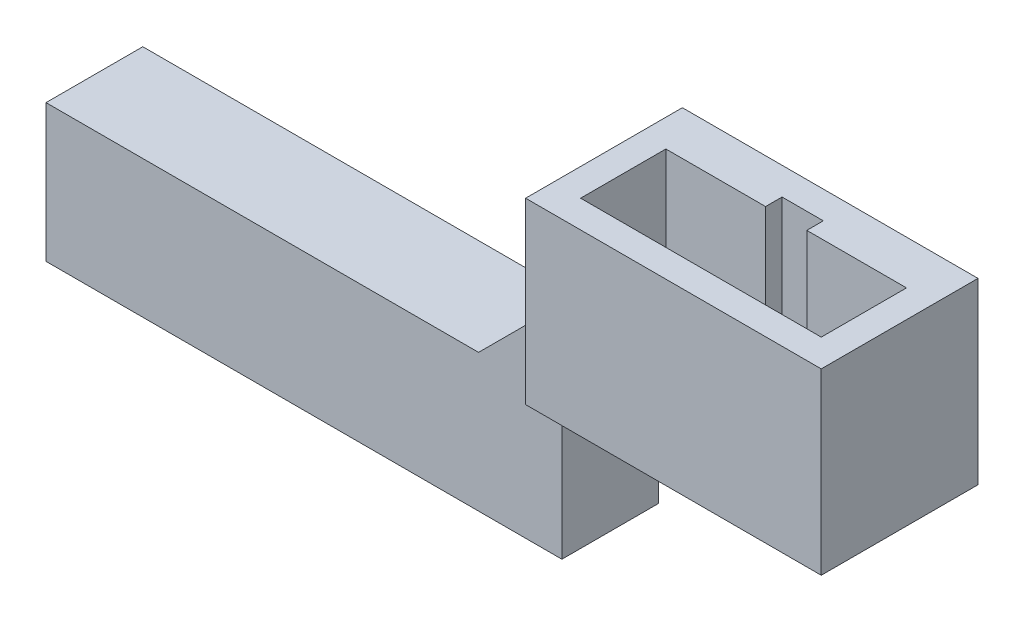
SolidWorks part; units mm, degrees
ref_plane "Front Plane" through (0, 0, 0) normal (0, 0, 1) x (1, 0, 0)
ref_plane "Top Plane" through (0, 0, 0) normal (0, 1, 0) x (1, 0, 0)
ref_plane "Right Plane" through (0, 0, 0) normal (1, 0, 0) x (0, 0, -1)
sketch "Sketch1" plane through (0, 0, 0) normal (0, 1, 0) x (1, 0, 0)
  line L0 (4.04, 3) -> (4.04, 1.5)
  line L1 (0, 0) -> (37.52, 0)
  line L2 (0, 0) -> (0, 7.04)
  line L3 (0, 7.04) -> (37.52, 7.04)
  line L5 (1.5, 3) -> (3, 3)
  line L6 (1.5, 3) -> (1.5, 1.5)
  line L7 (1.5, 1.5) -> (3, 1.5)
  line L8 (3, 3) -> (3, 1.5)
  line L9 (4.04, 3) -> (5.54, 3)
  line L10 (5.54, 3) -> (5.54, 1.5)
  line L11 (4.04, 1.5) -> (5.54, 1.5)
  line L12 (6.58, 3) -> (6.58, 1.5)
  line L13 (6.58, 3) -> (8.08, 3)
  line L14 (8.08, 3) -> (8.08, 1.5)
  line L15 (6.58, 1.5) -> (8.08, 1.5)
  line L16 (9.12, 3) -> (9.12, 1.5)
  line L17 (9.12, 3) -> (10.62, 3)
  line L18 (10.62, 3) -> (10.62, 1.5)
  line L19 (9.12, 1.5) -> (10.62, 1.5)
  line L20 (11.66, 3) -> (11.66, 1.5)
  line L21 (11.66, 3) -> (13.16, 3)
  line L22 (13.16, 3) -> (13.16, 1.5)
  line L23 (11.66, 1.5) -> (13.16, 1.5)
  line L24 (14.2, 3) -> (14.2, 1.5)
  line L25 (14.2, 3) -> (15.7, 3)
  line L26 (15.7, 3) -> (15.7, 1.5)
  line L27 (14.2, 1.5) -> (15.7, 1.5)
  line L28 (16.74, 3) -> (16.74, 1.5)
  line L29 (16.74, 3) -> (18.24, 3)
  line L30 (18.24, 3) -> (18.24, 1.5)
  line L31 (16.74, 1.5) -> (18.24, 1.5)
  line L32 (19.28, 3) -> (19.28, 1.5)
  line L33 (19.28, 3) -> (20.78, 3)
  line L34 (20.78, 3) -> (20.78, 1.5)
  line L35 (19.28, 1.5) -> (20.78, 1.5)
  line L36 (21.82, 3) -> (21.82, 1.5)
  line L37 (21.82, 3) -> (23.32, 3)
  line L38 (23.32, 3) -> (23.32, 1.5)
  line L39 (21.82, 1.5) -> (23.32, 1.5)
  line L40 (24.36, 3) -> (24.36, 1.5)
  line L41 (24.36, 3) -> (25.86, 3)
  line L42 (25.86, 3) -> (25.86, 1.5)
  line L43 (24.36, 1.5) -> (25.86, 1.5)
  line L44 (26.9, 3) -> (26.9, 1.5)
  line L45 (26.9, 3) -> (28.4, 3)
  line L46 (28.4, 3) -> (28.4, 1.5)
  line L47 (26.9, 1.5) -> (28.4, 1.5)
  line L48 (29.44, 3) -> (29.44, 1.5)
  line L49 (29.44, 3) -> (30.94, 3)
  line L50 (30.94, 3) -> (30.94, 1.5)
  line L51 (29.44, 1.5) -> (30.94, 1.5)
  line L52 (31.98, 3) -> (31.98, 1.5)
  line L53 (31.98, 3) -> (33.48, 3)
  line L54 (33.48, 3) -> (33.48, 1.5)
  line L55 (31.98, 1.5) -> (33.48, 1.5)
  line L56 (34.52, 3) -> (34.52, 1.5)
  line L57 (34.52, 3) -> (36.02, 3)
  line L58 (36.02, 3) -> (36.02, 1.5)
  line L59 (34.52, 1.5) -> (36.02, 1.5)
  line L144 (4.04, 5.54) -> (4.04, 4.04)
  line L145 (4.04, 5.54) -> (5.54, 5.54)
  line L146 (5.54, 5.54) -> (5.54, 4.04)
  line L147 (4.04, 4.04) -> (5.54, 4.04)
  line L148 (6.58, 5.54) -> (6.58, 4.04)
  line L149 (6.58, 5.54) -> (8.08, 5.54)
  line L150 (8.08, 5.54) -> (8.08, 4.04)
  line L151 (6.58, 4.04) -> (8.08, 4.04)
  line L152 (9.12, 5.54) -> (9.12, 4.04)
  line L153 (9.12, 5.54) -> (10.62, 5.54)
  line L154 (10.62, 5.54) -> (10.62, 4.04)
  line L155 (9.12, 4.04) -> (10.62, 4.04)
  line L156 (11.66, 5.54) -> (11.66, 4.04)
  line L157 (11.66, 5.54) -> (13.16, 5.54)
  line L158 (13.16, 5.54) -> (13.16, 4.04)
  line L159 (11.66, 4.04) -> (13.16, 4.04)
  line L160 (14.2, 5.54) -> (14.2, 4.04)
  line L161 (14.2, 5.54) -> (15.7, 5.54)
  line L162 (15.7, 5.54) -> (15.7, 4.04)
  line L163 (14.2, 4.04) -> (15.7, 4.04)
  line L164 (16.74, 5.54) -> (16.74, 4.04)
  line L165 (16.74, 5.54) -> (18.24, 5.54)
  line L166 (18.24, 5.54) -> (18.24, 4.04)
  line L167 (16.74, 4.04) -> (18.24, 4.04)
  line L168 (19.28, 5.54) -> (19.28, 4.04)
  line L169 (19.28, 5.54) -> (20.78, 5.54)
  line L170 (20.78, 5.54) -> (20.78, 4.04)
  line L171 (19.28, 4.04) -> (20.78, 4.04)
  line L172 (21.82, 5.54) -> (21.82, 4.04)
  line L173 (21.82, 5.54) -> (23.32, 5.54)
  line L174 (23.32, 5.54) -> (23.32, 4.04)
  line L175 (21.82, 4.04) -> (23.32, 4.04)
  line L176 (24.36, 5.54) -> (24.36, 4.04)
  line L177 (24.36, 5.54) -> (25.86, 5.54)
  line L178 (25.86, 5.54) -> (25.86, 4.04)
  line L179 (24.36, 4.04) -> (25.86, 4.04)
  line L180 (26.9, 5.54) -> (26.9, 4.04)
  line L181 (26.9, 5.54) -> (28.4, 5.54)
  line L182 (28.4, 5.54) -> (28.4, 4.04)
  line L183 (26.9, 4.04) -> (28.4, 4.04)
  line L184 (29.44, 5.54) -> (29.44, 4.04)
  line L185 (29.44, 5.54) -> (30.94, 5.54)
  line L186 (30.94, 5.54) -> (30.94, 4.04)
  line L187 (29.44, 4.04) -> (30.94, 4.04)
  line L188 (31.98, 5.54) -> (31.98, 4.04)
  line L189 (31.98, 5.54) -> (33.48, 5.54)
  line L190 (33.48, 5.54) -> (33.48, 4.04)
  line L191 (31.98, 4.04) -> (33.48, 4.04)
  line L192 (34.52, 5.54) -> (34.52, 4.04)
  line L193 (34.52, 5.54) -> (36.02, 5.54)
  line L194 (36.02, 5.54) -> (36.02, 4.04)
  line L195 (34.52, 4.04) -> (36.02, 4.04)
  line L280 (1.5, 5.54) -> (1.5, 4.04)
  line L281 (1.5, 5.54) -> (3, 5.54)
  line L282 (3, 5.54) -> (3, 4.04)
  line L283 (1.5, 4.04) -> (3, 4.04)
  line L284 (37.06, 3) -> (37.06, 1.5) [skipped]
  line L285 (37.06, 3) -> (38.56, 3) [skipped]
  line L286 (38.56, 3) -> (38.56, 1.5) [skipped]
  line L287 (37.06, 1.5) -> (38.56, 1.5) [skipped]
  line L288 (39.6, 3) -> (39.6, 1.5) [skipped]
  line L289 (39.6, 3) -> (41.1, 3) [skipped]
  line L290 (41.1, 3) -> (41.1, 1.5) [skipped]
  line L291 (39.6, 1.5) -> (41.1, 1.5) [skipped]
  line L292 (42.14, 3) -> (42.14, 1.5) [skipped]
  line L293 (42.14, 3) -> (43.64, 3) [skipped]
  line L294 (43.64, 3) -> (43.64, 1.5) [skipped]
  line L295 (42.14, 1.5) -> (43.64, 1.5) [skipped]
  line L296 (44.68, 3) -> (44.68, 1.5) [skipped]
  line L297 (44.68, 3) -> (46.18, 3) [skipped]
  line L298 (46.18, 3) -> (46.18, 1.5) [skipped]
  line L299 (44.68, 1.5) -> (46.18, 1.5) [skipped]
  line L300 (47.22, 3) -> (47.22, 1.5) [skipped]
  line L301 (47.22, 3) -> (48.72, 3) [skipped]
  line L302 (48.72, 3) -> (48.72, 1.5) [skipped]
  line L303 (47.22, 1.5) -> (48.72, 1.5) [skipped]
  line L304 (49.76, 3) -> (49.76, 1.5) [skipped]
  line L305 (49.76, 3) -> (51.26, 3) [skipped]
  line L306 (51.26, 3) -> (51.26, 1.5) [skipped]
  line L307 (49.76, 1.5) -> (51.26, 1.5) [skipped]
  line L308 (52.3, 3) -> (52.3, 1.5) [skipped]
  line L309 (52.3, 3) -> (53.8, 3) [skipped]
  line L310 (53.8, 3) -> (53.8, 1.5) [skipped]
  line L311 (52.3, 1.5) -> (53.8, 1.5) [skipped]
  line L312 (54.84, 3) -> (54.84, 1.5) [skipped]
  line L313 (54.84, 3) -> (56.34, 3) [skipped]
  line L314 (56.34, 3) -> (56.34, 1.5) [skipped]
  line L315 (54.84, 1.5) -> (56.34, 1.5) [skipped]
  line L316 (57.38, 3) -> (57.38, 1.5) [skipped]
  line L317 (57.38, 3) -> (58.88, 3) [skipped]
  line L318 (58.88, 3) -> (58.88, 1.5) [skipped]
  line L319 (57.38, 1.5) -> (58.88, 1.5) [skipped]
  line L320 (59.92, 3) -> (59.92, 1.5) [skipped]
  line L321 (59.92, 3) -> (61.42, 3) [skipped]
  line L322 (61.42, 3) -> (61.42, 1.5) [skipped]
  line L323 (59.92, 1.5) -> (61.42, 1.5) [skipped]
  line L324 (62.46, 3) -> (62.46, 1.5) [skipped]
  line L325 (62.46, 3) -> (63.96, 3) [skipped]
  line L326 (63.96, 3) -> (63.96, 1.5) [skipped]
  line L327 (62.46, 1.5) -> (63.96, 1.5) [skipped]
  line L328 (65, 3) -> (65, 1.5) [skipped]
  line L329 (65, 3) -> (66.5, 3) [skipped]
  line L330 (66.5, 3) -> (66.5, 1.5) [skipped]
  line L331 (65, 1.5) -> (66.5, 1.5) [skipped]
  line L332 (67.54, 3) -> (67.54, 1.5) [skipped]
  line L333 (67.54, 3) -> (69.04, 3) [skipped]
  line L334 (69.04, 3) -> (69.04, 1.5) [skipped]
  line L335 (67.54, 1.5) -> (69.04, 1.5) [skipped]
  line L336 (70.08, 3) -> (70.08, 1.5) [skipped]
  line L337 (70.08, 3) -> (71.58, 3) [skipped]
  line L338 (71.58, 3) -> (71.58, 1.5) [skipped]
  line L339 (70.08, 1.5) -> (71.58, 1.5) [skipped]
  line L340 (72.62, 3) -> (72.62, 1.5) [skipped]
  line L341 (72.62, 3) -> (74.12, 3) [skipped]
  line L342 (74.12, 3) -> (74.12, 1.5) [skipped]
  line L343 (72.62, 1.5) -> (74.12, 1.5) [skipped]
  line L344 (75.16, 3) -> (75.16, 1.5) [skipped]
  line L345 (75.16, 3) -> (76.66, 3) [skipped]
  line L346 (76.66, 3) -> (76.66, 1.5) [skipped]
  line L347 (75.16, 1.5) -> (76.66, 1.5) [skipped]
  line L348 (77.7, 3) -> (77.7, 1.5) [skipped]
  line L349 (77.7, 3) -> (79.2, 3) [skipped]
  line L350 (79.2, 3) -> (79.2, 1.5) [skipped]
  line L351 (77.7, 1.5) -> (79.2, 1.5) [skipped]
  line L352 (80.24, 3) -> (80.24, 1.5) [skipped]
  line L353 (80.24, 3) -> (81.74, 3) [skipped]
  line L354 (81.74, 3) -> (81.74, 1.5) [skipped]
  line L355 (80.24, 1.5) -> (81.74, 1.5) [skipped]
  line L356 (82.78, 3) -> (82.78, 1.5) [skipped]
  line L357 (82.78, 3) -> (84.28, 3) [skipped]
  line L358 (84.28, 3) -> (84.28, 1.5) [skipped]
  line L359 (82.78, 1.5) -> (84.28, 1.5) [skipped]
  line L360 (85.32, 3) -> (85.32, 1.5) [skipped]
  line L361 (85.32, 3) -> (86.82, 3) [skipped]
  line L362 (86.82, 3) -> (86.82, 1.5) [skipped]
  line L363 (85.32, 1.5) -> (86.82, 1.5) [skipped]
  line L364 (87.86, 3) -> (87.86, 1.5) [skipped]
  line L365 (87.86, 3) -> (89.36, 3) [skipped]
  line L366 (89.36, 3) -> (89.36, 1.5) [skipped]
  line L367 (87.86, 1.5) -> (89.36, 1.5) [skipped]
  line L368 (37.06, 5.54) -> (37.06, 4.04) [skipped]
  line L369 (37.06, 5.54) -> (38.56, 5.54) [skipped]
  line L370 (38.56, 5.54) -> (38.56, 4.04) [skipped]
  line L371 (37.06, 4.04) -> (38.56, 4.04) [skipped]
  line L372 (39.6, 5.54) -> (39.6, 4.04) [skipped]
  line L373 (39.6, 5.54) -> (41.1, 5.54) [skipped]
  line L374 (41.1, 5.54) -> (41.1, 4.04) [skipped]
  line L375 (39.6, 4.04) -> (41.1, 4.04) [skipped]
  line L376 (42.14, 5.54) -> (42.14, 4.04) [skipped]
  line L377 (42.14, 5.54) -> (43.64, 5.54) [skipped]
  line L378 (43.64, 5.54) -> (43.64, 4.04) [skipped]
  line L379 (42.14, 4.04) -> (43.64, 4.04) [skipped]
  line L380 (44.68, 5.54) -> (44.68, 4.04) [skipped]
  line L381 (44.68, 5.54) -> (46.18, 5.54) [skipped]
  line L382 (46.18, 5.54) -> (46.18, 4.04) [skipped]
  line L383 (44.68, 4.04) -> (46.18, 4.04) [skipped]
  line L384 (47.22, 5.54) -> (47.22, 4.04) [skipped]
  line L385 (47.22, 5.54) -> (48.72, 5.54) [skipped]
  line L386 (48.72, 5.54) -> (48.72, 4.04) [skipped]
  line L387 (47.22, 4.04) -> (48.72, 4.04) [skipped]
  line L388 (49.76, 5.54) -> (49.76, 4.04) [skipped]
  line L389 (49.76, 5.54) -> (51.26, 5.54) [skipped]
  line L390 (51.26, 5.54) -> (51.26, 4.04) [skipped]
  line L391 (49.76, 4.04) -> (51.26, 4.04) [skipped]
  line L392 (52.3, 5.54) -> (52.3, 4.04) [skipped]
  line L393 (52.3, 5.54) -> (53.8, 5.54) [skipped]
  line L394 (53.8, 5.54) -> (53.8, 4.04) [skipped]
  line L395 (52.3, 4.04) -> (53.8, 4.04) [skipped]
  line L396 (54.84, 5.54) -> (54.84, 4.04) [skipped]
  line L397 (54.84, 5.54) -> (56.34, 5.54) [skipped]
  line L398 (56.34, 5.54) -> (56.34, 4.04) [skipped]
  line L399 (54.84, 4.04) -> (56.34, 4.04) [skipped]
  line L400 (57.38, 5.54) -> (57.38, 4.04) [skipped]
  line L401 (57.38, 5.54) -> (58.88, 5.54) [skipped]
  line L402 (58.88, 5.54) -> (58.88, 4.04) [skipped]
  line L403 (57.38, 4.04) -> (58.88, 4.04) [skipped]
  line L404 (59.92, 5.54) -> (59.92, 4.04) [skipped]
  line L405 (59.92, 5.54) -> (61.42, 5.54) [skipped]
  line L406 (61.42, 5.54) -> (61.42, 4.04) [skipped]
  line L407 (59.92, 4.04) -> (61.42, 4.04) [skipped]
  line L408 (62.46, 5.54) -> (62.46, 4.04) [skipped]
  line L409 (62.46, 5.54) -> (63.96, 5.54) [skipped]
  line L410 (63.96, 5.54) -> (63.96, 4.04) [skipped]
  line L411 (62.46, 4.04) -> (63.96, 4.04) [skipped]
  line L412 (65, 5.54) -> (65, 4.04) [skipped]
  line L413 (65, 5.54) -> (66.5, 5.54) [skipped]
  line L414 (66.5, 5.54) -> (66.5, 4.04) [skipped]
  line L415 (65, 4.04) -> (66.5, 4.04) [skipped]
  line L416 (67.54, 5.54) -> (67.54, 4.04) [skipped]
  line L417 (67.54, 5.54) -> (69.04, 5.54) [skipped]
  line L418 (69.04, 5.54) -> (69.04, 4.04) [skipped]
  line L419 (67.54, 4.04) -> (69.04, 4.04) [skipped]
  line L420 (70.08, 5.54) -> (70.08, 4.04) [skipped]
  line L421 (70.08, 5.54) -> (71.58, 5.54) [skipped]
  line L422 (71.58, 5.54) -> (71.58, 4.04) [skipped]
  line L423 (70.08, 4.04) -> (71.58, 4.04) [skipped]
  line L424 (72.62, 5.54) -> (72.62, 4.04) [skipped]
  line L425 (72.62, 5.54) -> (74.12, 5.54) [skipped]
  line L426 (74.12, 5.54) -> (74.12, 4.04) [skipped]
  line L427 (72.62, 4.04) -> (74.12, 4.04) [skipped]
  line L428 (75.16, 5.54) -> (75.16, 4.04) [skipped]
  line L429 (75.16, 5.54) -> (76.66, 5.54) [skipped]
  line L430 (76.66, 5.54) -> (76.66, 4.04) [skipped]
  line L431 (75.16, 4.04) -> (76.66, 4.04) [skipped]
  line L432 (77.7, 5.54) -> (77.7, 4.04) [skipped]
  line L433 (77.7, 5.54) -> (79.2, 5.54) [skipped]
  line L434 (79.2, 5.54) -> (79.2, 4.04) [skipped]
  line L435 (77.7, 4.04) -> (79.2, 4.04) [skipped]
  line L436 (80.24, 5.54) -> (80.24, 4.04) [skipped]
  line L437 (80.24, 5.54) -> (81.74, 5.54) [skipped]
  line L438 (81.74, 5.54) -> (81.74, 4.04) [skipped]
  line L439 (80.24, 4.04) -> (81.74, 4.04) [skipped]
  line L440 (82.78, 5.54) -> (82.78, 4.04) [skipped]
  line L441 (82.78, 5.54) -> (84.28, 5.54) [skipped]
  line L442 (84.28, 5.54) -> (84.28, 4.04) [skipped]
  line L443 (82.78, 4.04) -> (84.28, 4.04) [skipped]
  line L444 (85.32, 5.54) -> (85.32, 4.04) [skipped]
  line L445 (85.32, 5.54) -> (86.82, 5.54) [skipped]
  line L446 (86.82, 5.54) -> (86.82, 4.04) [skipped]
  line L447 (85.32, 4.04) -> (86.82, 4.04) [skipped]
  line L448 (87.86, 5.54) -> (87.86, 4.04) [skipped]
  line L449 (87.86, 5.54) -> (89.36, 5.54) [skipped]
  line L450 (89.36, 5.54) -> (89.36, 4.04) [skipped]
  line L451 (87.86, 4.04) -> (89.36, 4.04) [skipped]
  line L452 (37.52, 7.04) -> (37.52, 0)
  dimension "D1" = 1.5
  dimension "D2" = 1.5
  dimension "D3" = 1.5
  dimension "D6" = 7.04
  dimension "D7" = 1.5
  dimension "D8" = 1.5
  dimension "D9" = 1.04
  dimension "D10" = 1.04
  dimension "D4" = 35
  dimension "D5" = 2
extrude "Boss-Extrude1" add sketch "Sketch1" along normal blind 8
sketch "Sketch2" plane through (0, 8, 0) normal (0, 1, 0) x (1, 0, 0)
  line L5 (0, 7.04) -> (37.52, 7.04)
  line L6 (0, 7.04) -> (0, 0)
  line L7 (0, 0) -> (37.52, 0)
  line L8 (37.52, 7.04) -> (37.52, 0)
extrude "Boss-Extrude2" add sketch "Sketch2" along normal blind 2
sketch "Sketch3" plane through (0, 10, 0) normal (0, 1, 0) x (1, 0, 0)
  line L0 (0, 3.52) -> (37.52, 3.52) construction
  line L1 (36.46, 9.82) -> (57.96, 9.82)
  line L2 (36.46, 9.82) -> (36.46, -1.58)
  line L3 (36.46, -1.58) -> (57.96, -1.58)
  line L4 (57.96, 9.82) -> (57.96, -1.58)
  line L5 (38.46, 6.62) -> (55.96, 6.62)
  line L6 (38.46, 6.62) -> (38.46, 0.42)
  line L7 (38.46, 0.42) -> (55.96, 0.42)
  line L8 (55.96, 6.62) -> (55.96, 0.42)
  line L9 (48.71, 6.62) -> (45.71, 6.62)
  line L10 (48.71, 6.62) -> (48.71, 7.82)
  line L11 (48.71, 7.82) -> (45.71, 7.82)
  line L12 (45.71, 6.62) -> (45.71, 7.82)
  line L13 (0, 7.04) -> (0, 0) construction
  line L14 (37.52, 0) -> (37.52, 7.04) construction
  line L15 (47.21, 0.42) -> (47.21, 6.62) construction
  line L16 (35.27, 3) -> (35.27, 1.5) construction
  line L17 (37.81, 3) -> (37.81, 1.5) construction
  line L18 (37.06, 3) -> (38.56, 3) construction
  line L19 (37.06, 3) -> (37.06, 1.5) construction
  line L20 (36.02, 3) -> (34.52, 3)
  line L21 (36.02, 1.5) -> (36.02, 3)
  line L22 (34.52, 1.5) -> (36.02, 1.5)
  line L23 (34.52, 3) -> (34.52, 1.5)
  line L24 (36.02, 3) -> (34.52, 3)
  line L25 (36.02, 1.5) -> (36.02, 3)
  line L26 (34.52, 1.5) -> (36.02, 1.5)
  line L27 (34.52, 3) -> (34.52, 1.5)
  line L28 (37.06, 1.5) -> (38.56, 1.5) construction
  line L29 (38.56, 3) -> (38.56, 1.5) construction
  line M31 (0, 0) -> (37.52, 0)
  line M32 (37.52, 0) -> (37.52, 7.04)
  line M33 (37.52, 7.04) -> (0, 7.04)
  dimension "D1" = 17.5
  dimension "D2" = 6.2
  dimension "D3" = 1.2
  dimension "D4" = 2
  dimension "D5" = 2
  dimension "D6" = 2
  dimension "D7" = 2
  dimension "D8" = 3
  dimension "D10" = 0.1
  dimension "D11" = 1.5
  dimension "D12" = 2.54
  dimension "D9" = 0
extrude "Boss-Extrude3" add sketch "Sketch3" along normal blind 13 contours L4 L1 L2 L3 L5 L12 L11 L10 L8 L7 L6 M33 M32 M31 | L2 M33 M31 M32
chamfer "Chamfer1" distance 5 angle 45 1 edges at (36.46, 10, -3.52)
